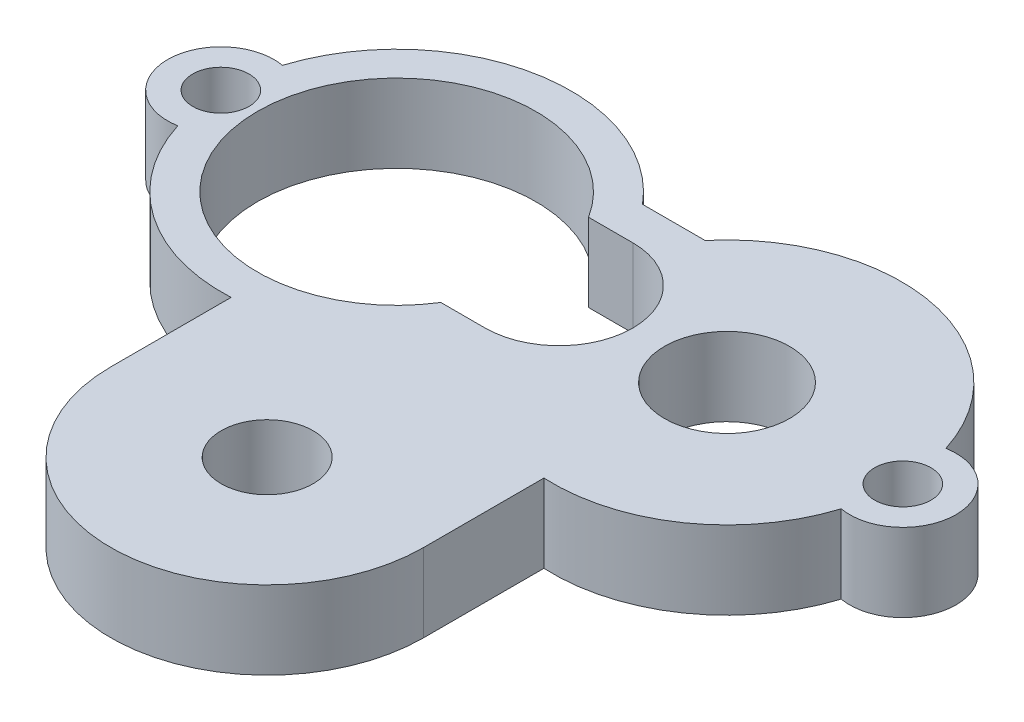
SolidWorks part; units mm, degrees
ref_plane "Front Plane" through (0, 0, 0) normal (0, 0, 1) x (1, 0, 0)
ref_plane "Top Plane" through (0, 0, 0) normal (0, 1, 0) x (1, 0, 0)
ref_plane "Right Plane" through (0, 0, 0) normal (1, 0, 0) x (0, 0, -1)
sketch "Sketch1" plane through (0, 0, 0) normal (0, 1, 0) x (1, 0, 0)
  line L0 (0, -6.35) -> (0, 24.8028) construction
  line L1 (-1.27, 16.51) -> (1.27, 16.51)
  line L2 (6.35, 0) -> (6.35, 4.8857)
  line L3 (-6.35, 0) -> (-6.35, 4.8857)
  line L4 (-6.35, 0) -> (-6.35, 46.0083) construction
  line L5 (0, 0) -> (0, 46.0083) construction
  line L6 (6.35, 0) -> (6.35, 46.0083) construction
  line L7 (-28.6102, 19.05) -> (31.923, 19.05) construction
  line L8 (-6.35, 19.0411) -> (-6.35, 19.05)
  line L9 (6.35, 19.0411) -> (6.35, 19.05)
  line L10 (-13.843, 11.9634) -> (13.843, 11.9634) construction
  line L11 (-16.002, 27.7742) -> (-16.002, 10.802) construction
  line L12 (16.002, 27.7742) -> (16.002, 6.8989) construction
  line L13 (0, 11.9634) -> (-16.002, 11.9634) construction
  line L14 (0, 11.9634) -> (16.002, 11.9634) construction
  arc A0 (-6.35, 0) -> (6.35, 0) centre (0, 0) ccw
  circle A1 centre (0, 0) radius 1.8669
  arc A2 (6.35, 4.8857) -> (13.4661, 9.8376) centre (6.7058, 11.9634) ccw
  arc A3 (-6.35, 4.8857) -> (-13.4661, 9.8376) centre (-6.7058, 11.9634) cw
  arc A4 (-13.4661, 14.0892) -> (-13.4661, 9.8376) centre (-13.843, 11.9634) ccw
  circle A5 centre (-13.843, 11.9634) radius 1.143
  circle A6 centre (13.843, 11.9634) radius 1.143
  arc A7 (13.4661, 14.0892) -> (13.4661, 9.8376) centre (13.843, 11.9634) cw
  arc A8 (-13.4661, 14.0892) -> (-1.27, 16.51) centre (-6.7058, 11.9634) cw
  arc A9 (13.4661, 14.0892) -> (1.27, 16.51) centre (6.7058, 11.9634) ccw
  point P44 (-13.843, 11.9634)
  dimension "D2" = 3.7338
  dimension "D4" = 14.1732
  dimension "D8" = 27.686
  dimension "D9" = 2.286
  dimension "D1" = 12.7
  dimension "D3" = 25.4
  dimension "D5" = 2.54
  dimension "D6" = 2.54
  dimension "D7" = 32.004
extrude "Boss-Extrude1" add sketch "Sketch1" along normal blind 3.175 contours A7 A9 L1 A8 A4 A3 L3 A0 L2 A2 A6 A5 A1
sketch "Sketch2" plane through (0, 3.175, 0) normal (0, 1, 0) x (1, 0, 0)
  line L0 (-6.7058, 11.9634) -> (-0.1145, 11.9634) construction
  line L1 (-0.1145, 8.9662) -> (-1.9146, 8.9662)
  line L2 (-0.1145, 14.9606) -> (-1.9146, 14.9606)
  arc A0 (-1.9146, 14.9606) -> (-1.9146, 8.9662) centre (-6.7058, 11.9634) ccw
  arc A1 (-0.1145, 8.9662) -> (-0.1145, 14.9606) centre (-0.1145, 11.9634) ccw
  circle A2 centre (6.7058, 11.9634) radius 2.54
  dimension "D1" = 11.303
  dimension "D2" = 5.9944
  dimension "D3" = 15.24
  dimension "D4" = 5.08
extrude "Cut-Extrude1" cut sketch "Sketch2" against normal through all
